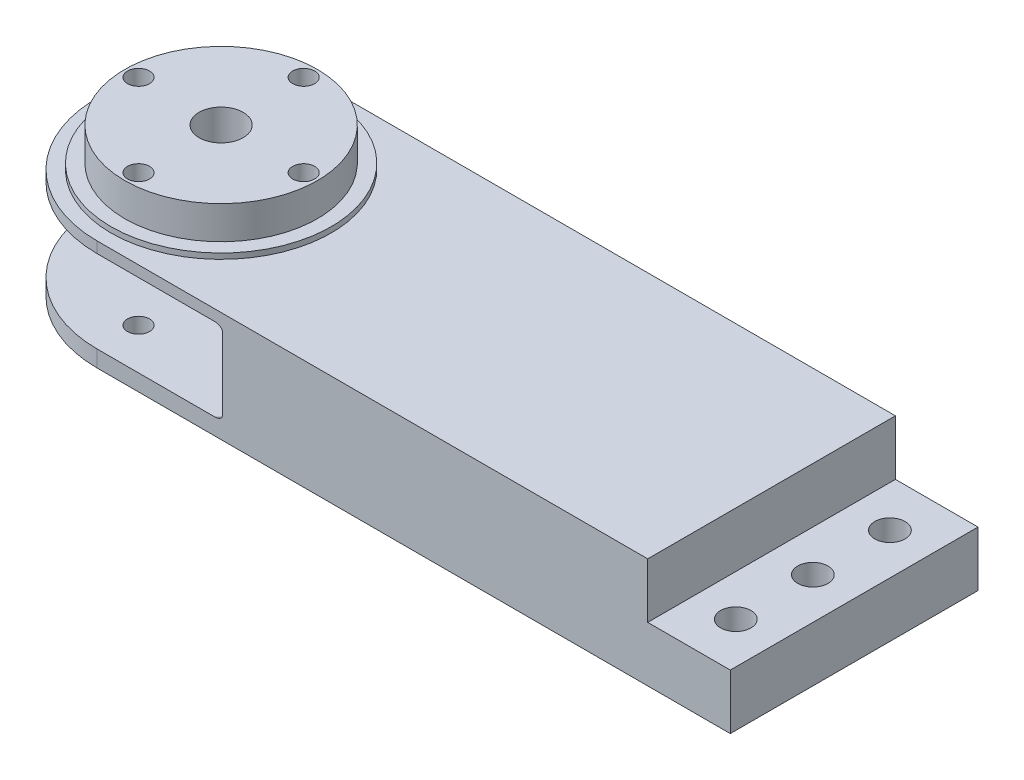
SolidWorks part; units mm, degrees
ref_plane "Front" through (0, 0, 0) normal (0, 0, 1) x (1, 0, 0)
ref_plane "Top" through (0, 0, 0) normal (0, 1, 0) x (1, 0, 0)
ref_plane "Right" through (0, 0, 0) normal (1, 0, 0) x (0, 0, -1)
sketch "草图2" plane through (0, 0, 0) normal (0, 1, 0) x (1, 0, 0)
  line L0 (-36.5127, 0) -> (106.694, 0) construction
  line L1 (0, 40.2193) -> (0, -44.2713) construction
  line L2 (0, 22.5) -> (100, 22.5)
  line L3 (100, 22.5) -> (100, -22.5)
  line L4 (100, -22.5) -> (0, -22.5)
  circle A0 centre (0, 0) radius 22.5 construction
  circle A1 centre (-15, 0) radius 1.5
  circle A2 centre (0, 15) radius 1.5
  circle A3 centre (15, 0) radius 1.5
  circle A4 centre (0, -15) radius 1.5
  arc A5 (0, 22.5) -> (0, -22.5) centre (0, 0) ccw
  point P18 (0, 0)
  dimension "D1" = 45
  dimension "D2" = 3
  dimension "D5" = 100
  dimension "D3" = 15
  dimension "D4" = 4
extrude "凸台-拉伸1" add sketch "草图2" along normal blind 20 contours A0
sketch "草图4" plane through (0, 0, 0) normal (0, 1, 0) x (1, 0, 0)
  circle A0 centre (0, 0) radius 32
  dimension "D1" = 64
extrude "切除-拉伸1" cut sketch "草图4" along normal blind 15 from offset 3
sketch "草图5" plane through (0, 0, 0) normal (0, 0, 1) x (1, 0, 0)
  line L0 (0, 42.2153) -> (0, -8.7676) construction
  line L1 (0, 20) -> (-20, 20)
  line L2 (0, 20) -> (-22.5, 20) construction
  line L3 (-20, 20) -> (-20, 21)
  line L4 (-20, 21) -> (-17.5, 21)
  line L5 (-17.5, 21) -> (-17.5, 27)
  line L6 (-17.5, 27) -> (0, 27)
  line L7 (0, 27) -> (0, 20)
  dimension "D1" = 20
  dimension "D2" = 1
  dimension "D3" = 17.5
  dimension "D4" = 6
revolve "旋转1" add sketch "草图5" angle 360 about L0
sketch "草图6" plane through (0, 0, 0) normal (0, 1, 0) x (1, 0, 0)
  line L0 (0, 29.2235) -> (0, -27.4994) construction
  circle A0 centre (0, 15) radius 2
  circle A1 centre (15, 0) radius 2
  circle A2 centre (0, -15) radius 2
  circle A3 centre (-15, 0) radius 2
  circle A4 centre (0, 0) radius 4
  point P14 (0, 0)
  dimension "D1" = 4
  dimension "D4" = 8
  dimension "D2" = 15
  dimension "D3" = 4
extrude "切除-拉伸2" cut sketch "草图6" along normal through all
sketch "草图8" plane through (0, 0, 0) normal (0, 1, 0) x (1, 0, 0)
  line L0 (107.5, 22.5) -> (107.5, -22.5) construction
  line L1 (100, -22.5) -> (115, -22.5)
  line L2 (100, -22.5) -> (100, 22.5)
  line L3 (100, 22.5) -> (115, 22.5)
  line L4 (115, -22.5) -> (115, 22.5)
  line L5 (51.9773, 0) -> (93.7645, 0) construction
  point P11 (107.5, 0)
  point P12 (107.5, 14)
  point P13 (0, 0)
  point P14 (107.5, -14)
  dimension "D2" = 14
  dimension "D1" = 15
extrude "凸台-拉伸3" add sketch "草图8" along normal blind 10 contours L4 L3 L2 L1
hole_wizard "M5 六角头螺栓的柱形沉头孔1" positions "草图9" profile "草图10" counterbore size "M5" standard "GB" end condition through all
sketch "草图9" plane through (0, 0, 0) normal (0, -1, 0) x (-1, 0, 0)
  point P0 (-107.5, -14)
  point P3 (-107.5, 0)
  point P6 (-107.5, 14)
sketch "草图10" plane through (107.5, 0, 14) normal (1, 0, 0) x (0, 0, -1)
  line L0 (0, 0) -> (0, 27)
  line L1 (0, 27) -> (2.75, 27)
  line L3 (2.75, 27) -> (2.75, 0.5)
  line L4 (2.75, 0.5) -> (5.5, 0.5)
  line L5 (5.5, 0.5) -> (5.5, 0)
  line L7 (5.5, 0) -> (0, 0)
  line L11 (0, -6.35) -> (0, 107.95) construction
  dimension "通孔孔直径" = 5.5
  dimension "通孔孔深度" = 27
  dimension "柱形沉头孔直径" = 11
  dimension "柱形沉头孔深度" = 0.5
fillet "圆角1" radius 1 2 edges at (32, 3, 0) (32, 18, 0)
